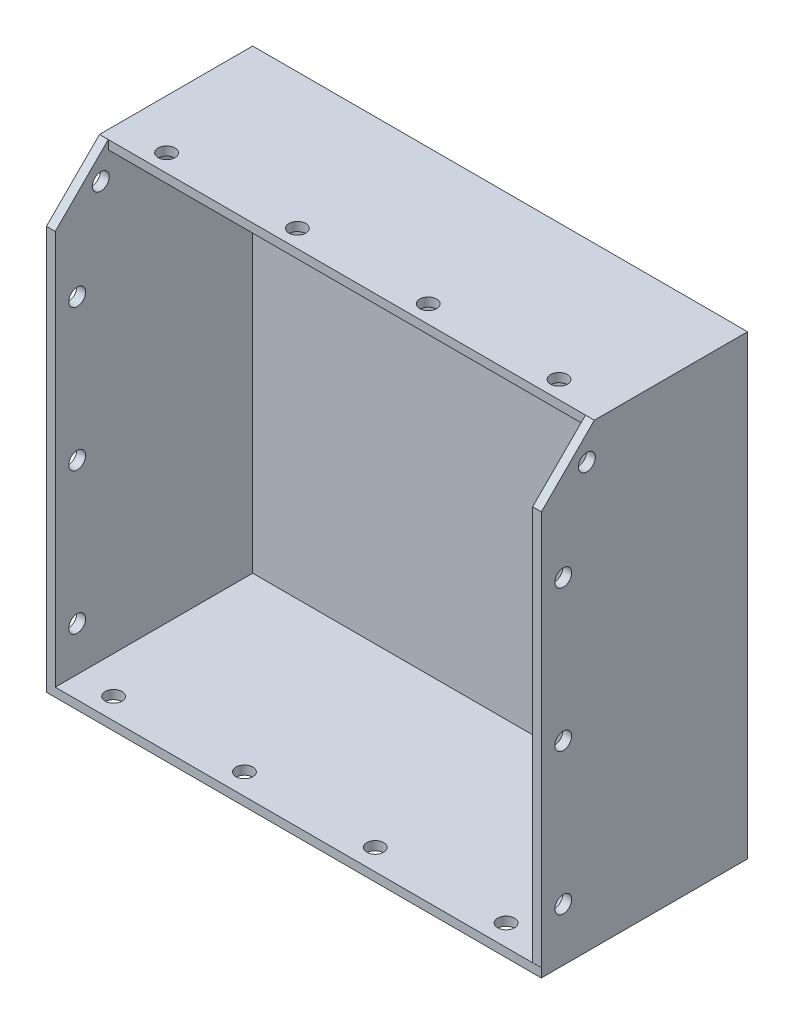
SolidWorks part; units mm, degrees
material "Custom Plastic"
ref_plane "X-Y Datum" through (0, 0, 0) normal (0, 0, 1) x (1, 0, 0)
ref_plane "X-Z Datum" through (0, 0, 0) normal (0, 1, 0) x (1, 0, 0)
ref_plane "Y-Z Datum" through (0, 0, 0) normal (1, 0, 0) x (0, 0, -1)
sketch "Sketch2" plane through (0, 0, 0) normal (0, 0, 1) x (1, 0, 0)
  line L1 (-105.8757, -82) -> (105.8757, -82)
  line L2 (-105.8757, -82) -> (-105.8757, 82)
  line L3 (-105.8757, 82) -> (105.8757, 82)
  line L4 (105.8757, -82) -> (105.8757, 82)
  line L5 (-105.8757, -82) -> (105.8757, 82) construction
  line L6 (-105.8757, 82) -> (105.8757, -82) construction
  point P0 (0, 0)
extrude "Boss-Extrude1" add sketch "Sketch2" along normal blind 74.0833
sketch "Sketch9" plane through (0, 0, 74.0833) normal (0, 0, 1) x (1, 0, 0)
  line L0 (-105.8757, -47.7482) -> (-102.7007, -47.7482)
  line L1 (-105.8757, 82) -> (-105.8757, -82) construction
  line L2 (-61.2665, -82) -> (-61.2665, -78.825)
  line L3 (-105.8757, -82) -> (105.8757, -82) construction
  line L4 (105.8757, -21.963) -> (102.7007, -21.963)
  line L5 (105.8757, -82) -> (105.8757, 82) construction
  line L6 (-87.7618, 82) -> (-87.7618, 78.825)
  line L7 (105.8757, 82) -> (-105.8757, 82) construction
  line L8 (-102.7007, 62.95) -> (-102.7007, 78.825)
  line L9 (-102.7007, -82) -> (-102.7007, 62.95)
  line L10 (-61.2665, -78.825) -> (-102.7007, -78.825)
  line L11 (-61.2665, -78.825) -> (102.7007, -78.825)
  line L12 (102.7007, -78.825) -> (102.7007, 82)
  line L13 (-102.7007, 78.825) -> (102.7007, 78.825)
extrude "Cut-Extrude7" cut sketch "Sketch9" against normal blind 70.9083
sketch "Sketch11" plane through (-105.8757, 0, 0) normal (-1, 0, 0) x (0, 0, 1)
  line L0 (74.0833, 62.95) -> (55.0333, 62.95)
  line L1 (74.0833, 82) -> (74.0833, -82) construction
  line L2 (55.0333, 62.95) -> (55.0333, 82)
  line L3 (74.0833, 82) -> (0, 82) construction
  line L4 (55.0333, 82) -> (74.0833, 62.95)
  line L5 (55.0333, 82) -> (74.0833, 82)
  line L6 (74.0833, 82) -> (74.0833, 62.95)
  line L7 (55.0333, 79.6238) -> (58.2083, 79.6238)
  line L8 (58.2083, 78.825) -> (58.2083, 82)
  line M5 (74.0833, -82) -> (74.0833, 82)
  line M6 (74.0833, 82) -> (0, 82)
extrude "Cut-Extrude9" cut sketch "Sketch11" against normal up to next contours L8 L4 M5 M6
sketch "Sketch13" plane through (-105.8757, 0, 0) normal (-1, 0, 0) x (0, 0, 1)
  line L0 (58.2083, 78.825) -> (55.0333, 82)
  line L1 (58.2083, 82) -> (0, 82) construction
  line L2 (55.0333, 82) -> (58.2083, 82)
  line L3 (58.2083, 82) -> (58.2083, 78.825)
extrude "Cut-Extrude10" cut sketch "Sketch13" against normal blind 3.175
sketch "Sketch14" plane through (0, 0, 58.2083) normal (0, 0, 1) x (1, 0, 0)
  line L1 (-102.7007, 82) -> (102.7007, 82)
  line L2 (-102.7007, 82) -> (-102.7007, 78.825)
  line L3 (-102.7007, 78.825) -> (102.7007, 78.825)
  line L4 (102.7007, 82) -> (102.7007, 78.825)
extrude "Cut-Extrude11" cut sketch "Sketch14" against normal blind 3.175
sketch "Sketch15" plane through (105.8757, 0, 0) normal (1, 0, 0) x (0, 0, -1)
  line L0 (-58.2083, 78.825) -> (-55.0333, 82)
  line L1 (-55.0333, 82) -> (-58.2083, 82)
  line L2 (-58.2083, 82) -> (-58.2083, 79.2157)
  line L3 (-58.2083, 82) -> (-58.2083, 78.825) construction
extrude "Cut-Extrude12" cut sketch "Sketch15" against normal blind 3.175 and the other way through all
sketch "Sketch16" plane through (-105.8757, 0, 0) normal (-1, 0, 0) x (0, 0, 1)
  line L0 (66.2093, -68.9821) -> (74.0833, -68.9821)
  line L2 (74.0833, 62.95) -> (74.0833, -82) construction
  line L3 (66.2093, -82) -> (66.2093, -62.95)
  line L4 (74.0833, -82) -> (0, -82) construction
  circle A0 centre (66.2093, -62.95) radius 3.025
  dimension "D1" = 7.874
  dimension "D2" = 19.05
sketch "Sketch18" plane through (0, -82, 0) normal (0, -1, 0) x (1, 0, 0)
  line L0 (-89.3657, 74.0833) -> (-89.3657, 66.4633)
  line L1 (-105.8757, 74.0833) -> (105.8757, 74.0833) construction
  line L2 (-89.3657, 66.4633) -> (-105.8757, 66.4633)
  line L3 (-105.8757, 74.0833) -> (-105.8757, 0) construction
  circle A0 centre (-89.3657, 66.4633) radius 3.025
  dimension "D1" = 7.62
  dimension "D2" = 16.51
extrude "Cut-Extrude14" cut sketch "Sketch18" against normal up to next contours A0
pattern_linear "LPattern2" count 4 spacing 46.99 along (1, 0, 0) of "Cut-Extrude14"
sketch "Sketch19" plane through (0, 82, 0) normal (0, 1, 0) x (1, 0, 0)
  line L0 (-105.8757, -48.6833) -> (-88.1257, -48.6833)
  line L1 (-105.8757, -55.0333) -> (-105.8757, 0) construction
  line L2 (-97.0007, -48.6833) -> (-97.0007, -55.0333)
  line L3 (102.7007, -55.0333) -> (-102.7007, -55.0333) construction
  circle A0 centre (-88.1257, -48.6833) radius 3.025
  dimension "D1" = 17.75
  dimension "D2" = 6.35
extrude "Cut-Extrude15" cut sketch "Sketch19" against normal up to next
pattern_linear "LPattern3" count 4 spacing 46.99 along (1, 0, 0) of "Cut-Extrude15"
sketch "Sketch20" plane through (-105.8757, 0, 0) normal (-1, 0, 0) x (0, 0, 1)
  line L2 (62.2175, 74.8158) -> (57.7274, 70.3257)
  line L3 (55.0333, 82) -> (74.0833, 62.95) construction
  line L4 (62.2175, 74.8158) -> (55.0333, 82)
  circle A0 centre (57.7274, 70.3257) radius 3.025
  dimension "D1" = 6.35
  dimension "D2" = 10.16
sketch "Sketch22" plane through (0, 0, 3.175) normal (0, 0, 1) x (1, 0, 0)
  line L2 (68.7173, 46.4031) -> (68.7173, 78.825)
  line L3 (-102.7007, 78.825) -> (102.7007, 78.825) construction
  line L4 (68.7173, 46.4031) -> (68.7173, -78.825)
  line L5 (102.7007, -78.825) -> (-102.7007, -78.825) construction
  line L7 (71.8923, -78.825) -> (71.8923, 78.825)
  line L8 (71.8923, 78.825) -> (68.7173, 78.825)
  line L9 (71.8923, -78.825) -> (68.7173, -78.825)
extrude "Boss-Extrude2" add sketch "Sketch22" along normal blind 70.866
sketch "Sketch23" plane through (0, 0, 74.0833) normal (0, 0, 1) x (1, 0, 0)
  line L0 (102.7007, 62.95) -> (71.8923, 62.95)
  line L1 (71.8923, -78.825) -> (71.8923, 78.825) construction
sketch "Sketch25" plane through (0, 78.825, 0) normal (0, 1, 0) x (1, 0, 0)
  line L0 (71.8923, -74.041) -> (71.8923, -55.0333) construction
  line L1 (71.8923, -55.0333) -> (68.7173, -55.0333)
  line L2 (71.8923, -55.0333) -> (71.8923, -74.041)
  line L3 (71.8923, -74.041) -> (68.7173, -74.041)
  line L4 (68.7173, -55.0333) -> (68.7173, -74.041)
  line L5 (68.7173, -55.0333) -> (71.8923, -55.0333) construction
extrude "Boss-Extrude3" add sketch "Sketch25" along normal blind 3.175
sketch "Sketch26" plane through (71.8923, 0, 0) normal (1, 0, 0) x (0, 0, -1)
  line L0 (-74.0833, 62.95) -> (-55.0333, 82)
  line L1 (-74.0833, 62.95) -> (-74.041, 82)
  line L2 (-74.041, 82) -> (-55.0333, 82)
extrude "Cut-Extrude18" cut sketch "Sketch26" against normal up to next
sketch "Sketch27" plane through (0, 0, 74.0833) normal (0, 0, 1) x (1, 0, 0)
  line L0 (71.8923, -78.825) -> (71.8923, -82)
  line L1 (-105.8757, -82) -> (105.8757, -82) construction
  line L2 (71.8923, -82) -> (105.8757, -82)
  line L3 (105.8757, -82) -> (105.8757, 82)
  line L4 (105.8757, 82) -> (71.8923, 82)
  line L5 (71.8923, 82) -> (71.8923, -78.825)
extrude "Cut-Extrude19" cut sketch "Sketch27" against normal up to next
extrude "Cut-Extrude20" cut sketch "Sketch16" against normal through all contours A0
pattern_linear "LPattern4" count 3 spacing 50.8 along (0, 1, 0) of "Cut-Extrude20"
extrude "Cut-Extrude21" cut sketch "Sketch20" against normal through all
equation "\"0.13i25\"=0.13"
